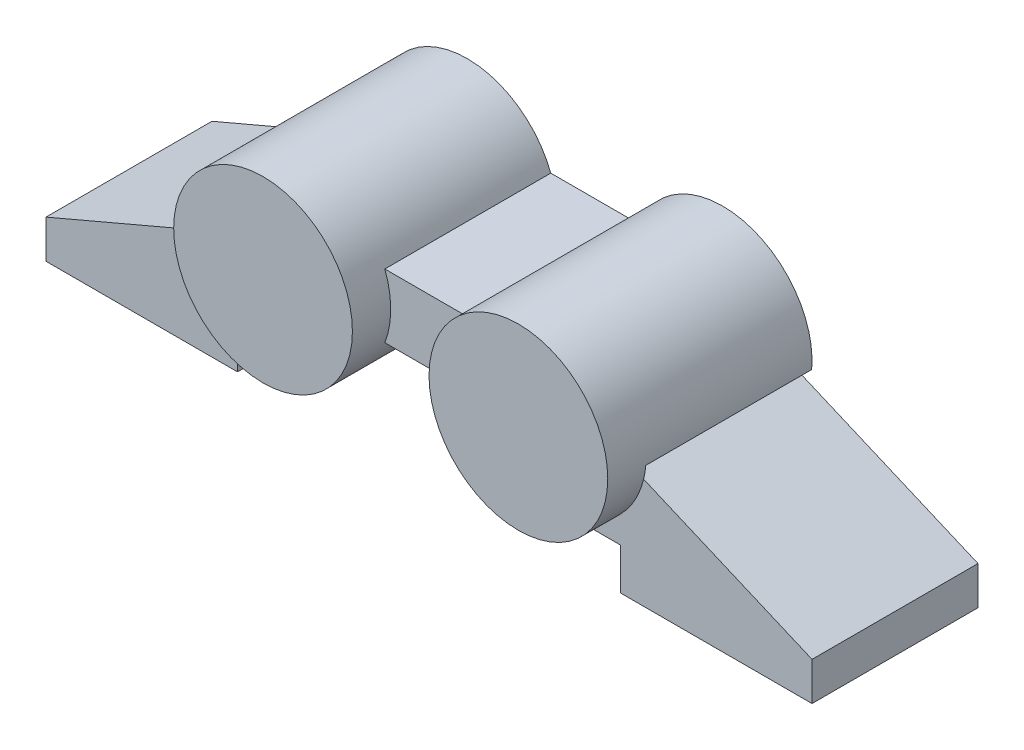
SolidWorks part; units mm, degrees
ref_plane "Front Plane" through (0, 0, 0) normal (0, 0, 1) x (1, 0, 0)
ref_plane "Top Plane" through (0, 0, 0) normal (0, 1, 0) x (1, 0, 0)
ref_plane "Right Plane" through (0, 0, 0) normal (1, 0, 0) x (0, 0, -1)
sketch "Sketch1" plane through (0, 0, 0) normal (0, 0, 1) x (1, 0, 0)
  line L0 (0, -47.8538) -> (0, 47.8538) construction
  line L1 (10, -14.5) -> (15, -14.5)
  line L2 (15, -14.5) -> (15, -17.75)
  line L3 (15, -17.75) -> (30, -17.75)
  line L4 (30, -17.75) -> (30, -14.75)
  line L5 (30, -14.75) -> (13, -7.5) construction
  line L6 (0, -5) -> (3.4617, -5)
  line L7 (3.4617, -5) -> (3.4617, -10) construction
  line L8 (3.4617, -10) -> (0, -10)
  line L9 (30, -14.75) -> (16.8089, -9.1244)
  line L10 (0, -10) -> (0, -5)
  circle A0 centre (10, -7.5) radius 7
  point P5 (0, 0)
  point P15 (3.4617, -7.5)
  dimension "D1" = 14
  dimension "D2" = 20
  dimension "D3" = 15
  dimension "D4" = 3
  dimension "D5" = 3.25
  dimension "D6" = 7.5
  dimension "D7" = 30
  dimension "D8" = 3
  dimension "D9" = 5
extrude "Boss-Extrude1" add sketch "Sketch1" along normal blind 13 contours A0 L1 L2 L3 L4 L9 | A0 | A0 L6 L10 L8
sketch "Sketch2" plane through (0, 0, 13) normal (0, 0, 1) x (1, 0, 0)
  circle A0 centre (10, -7.5) radius 7 construction
  circle A1 centre (10, -7.5) radius 7
extrude "Boss-Extrude2" add sketch "Sketch2" along normal blind 3
sketch "Sketch3" plane through (0, 0, 0) normal (0, 0, 1) x (1, 0, 0)
  line L0 (17.2012, -8.2045) -> (12.7528, -6.3074)
  line L1 (17.2012, -8.2045) -> (16.8089, -9.1244)
  line L2 (12.7528, -6.3074) -> (12.3605, -7.2273) construction
  line L3 (16.8089, -9.1244) -> (12.3605, -7.2273) construction
  line L4 (17.2012, -8.2045) -> (12.3605, -7.2273) construction
  line L5 (12.7528, -6.3074) -> (16.8089, -9.1244) construction
  line L6 (30, -14.75) -> (16.8089, -9.1244) construction
  line L7 (16.8089, -9.1244) -> (13, -7.5)
  circle A0 centre (10, -7.5) radius 7 construction
  circle A1 centre (10, -7.5) radius 7 construction
  circle A2 centre (10, -7.5) radius 3
  arc A3 (16.8089, -9.1244) -> (3.4617, -5) centre (10, -7.5) ccw construction
  point P5 (14.7808, -7.7159)
  dimension "D1" = 6
  dimension "D2" = 1
extrude "Cut-Extrude1" cut sketch "Sketch3" along normal blind 13 contours A2 | A2 L7 L1 L0
mirror "Mirror1" about plane through (0, 0, 0) normal (1, 0, 0) of bodies 108
